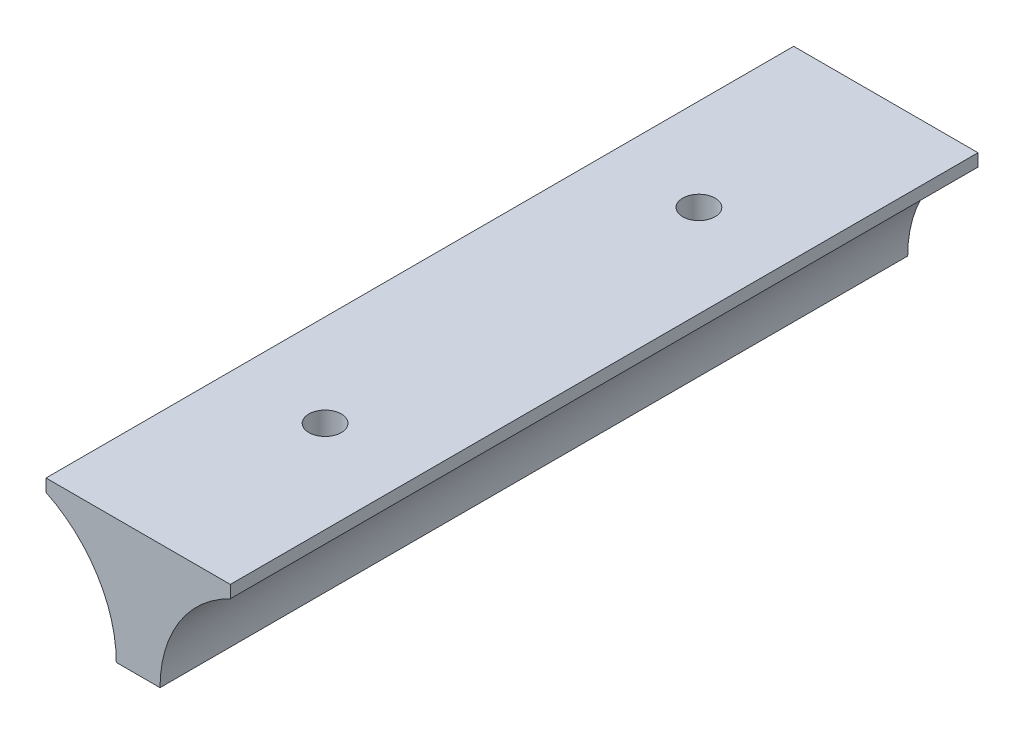
SolidWorks part; units mm, degrees
ref_plane "Front" through (0, 0, 0) normal (0, 0, 1) x (1, 0, 0)
ref_plane "Top" through (0, 0, 0) normal (0, 1, 0) x (1, 0, 0)
ref_plane "Right" through (0, 0, 0) normal (1, 0, 0) x (0, 0, -1)
sketch "Sketch1" plane through (0, 0, 0) normal (0, 0, 1) x (1, 0, 0)
  line L0 (-1.7545, 0) -> (1.7545, 0)
  line L1 (7.3956, 9) -> (7.3956, 10)
  line L2 (7.3956, 10) -> (-7.3956, 10)
  line L3 (-7.3956, 10) -> (-7.3956, 9)
  arc A0 (1.7545, 0) -> (7.3956, 9) centre (11.7545, 0) cw
  arc A1 (-1.7545, 0) -> (-7.3956, 9) centre (-11.7545, 0) ccw
  point P9 (0, 0)
  point P10 (0, 10)
  dimension "D1" = 10
  dimension "D2" = 10
  dimension "D3" = 3.509
  dimension "D4" = 1
extrude "Boss-Extrude1" add sketch "Sketch1" along normal blind 60
sketch "Sketch2" plane through (0, 10, 0) normal (0, 1, 0) x (1, 0, 0)
  line L0 (0, -60) -> (0, 0) construction
  line L1 (7.3956, -60) -> (-7.3956, -60) construction
  line L2 (7.3956, 0) -> (-7.3956, 0) construction
  point P6 (0, -45)
  point P7 (0, -15)
  dimension "D1" = 15
  dimension "D2" = 15
hole_wizard "Ø2.6 (2.6) Diameter Hole1" positions "3DSketch1" profile "Sketch3" hole size "Ø2.6" standard "ANSI Metric" end condition up to next
sketch3d "3DSketch1"
  point P0 (0, 10, 45)
  point P3 (0, 10, 15)
sketch "Sketch3" plane through (0, 10, 45) normal (1, 0, 0) x (0, 0, 1)
  line L0 (0, 0) -> (0, 10)
  line L1 (0, 10) -> (1.3, 10)
  line L2 (1.3, 10) -> (1.3, 0)
  line L5 (1.3, 0) -> (0, 0)
  line L11 (0, -6.35) -> (0, 107.95) construction
  dimension "Thru Hole Dia." = 2.6
  dimension "Thru Hole Depth" = 10
